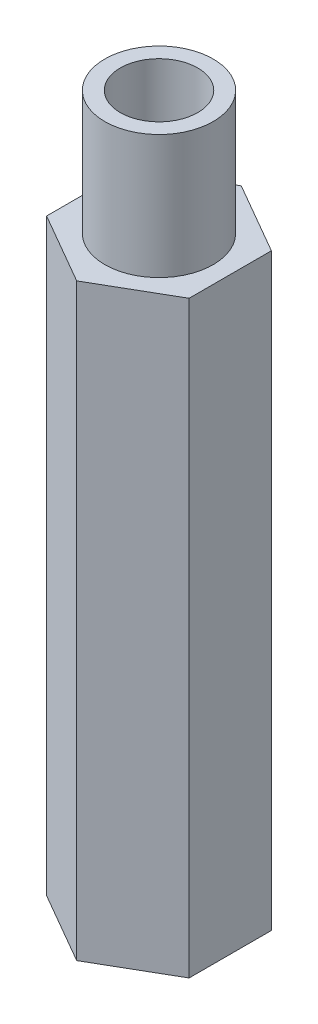
SolidWorks part; units mm, degrees
ref_plane "前视基准面" through (0, 0, 0) normal (0, 0, 1) x (1, 0, 0)
ref_plane "上视基准面" through (0, 0, 0) normal (0, 1, 0) x (1, 0, 0)
ref_plane "右视基准面" through (0, 0, 0) normal (1, 0, 0) x (0, 0, -1)
other "Configuration Table"
sketch "草图1" plane through (0, 0, 0) normal (0, 1, 0) x (1, 0, 0)
  line L1 (0, 2.6558) -> (-2.3, 1.3279)
  line L2 (-2.3, 1.3279) -> (-2.3, -1.3279)
  line L3 (-2.3, -1.3279) -> (0, -2.6558)
  line L4 (0, -2.6558) -> (2.3, -1.3279)
  line L5 (2.3, -1.3279) -> (2.3, 1.3279)
  line L6 (2.3, 1.3279) -> (0, 2.6558)
  circle A0 centre (0, 0) radius 2.3 construction
  dimension "D1" = 4.6
extrude "凸台-拉伸1" add sketch "草图1" along normal blind 19
sketch "草图2" plane through (0, 19, 0) normal (0, 1, 0) x (1, 0, 0)
  circle A0 centre (0, 0) radius 1.75
  dimension "D1" = 3.5
extrude "凸台-拉伸2" add sketch "草图2" along normal blind 4
cosmetic thread "装饰螺纹线1" parameters "D2"=3
hole_wizard "M3 螺纹孔1" positions "草图3" profile "草图4" tap size "M3" standard "GB" end condition through all
sketch "草图3" plane through (0, 23, 0) normal (0, 1, 0) x (1, 0, 0)
  point P0 (0, 0)
sketch "草图4" plane through (0, 23, 0) normal (1, 0, 0) x (0, 0, 1)
  line L0 (0, 0) -> (0, 23)
  line L1 (0, 23) -> (1.25, 23)
  line L2 (1.25, 23) -> (1.25, 0)
  line L5 (1.25, 0) -> (0, 0)
  line L11 (0, -6.35) -> (0, 107.95) construction
  dimension "通孔螺纹孔钻头直径" = 2.5
  dimension "通孔螺纹孔钻头深度" = 23
cosmetic thread "孔螺蚊线1" parameters "D2"=3
